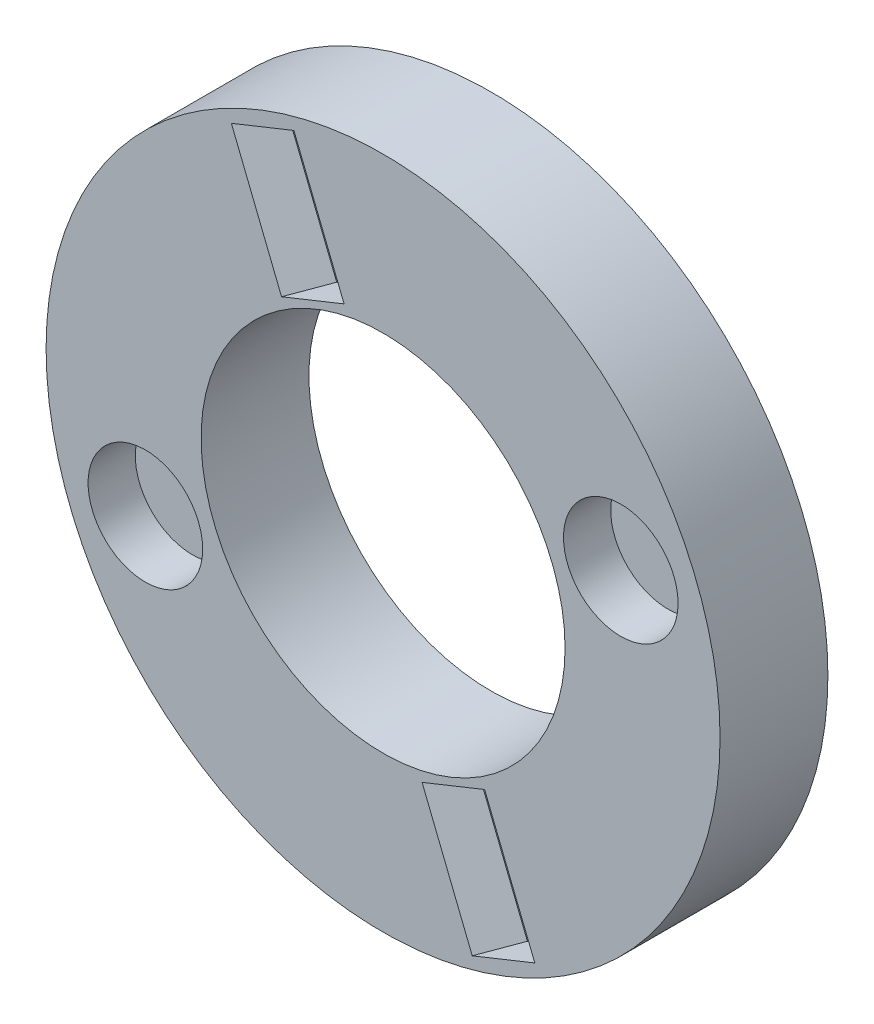
SolidWorks part; units mm, degrees
ref_plane "Plan de face" through (0, 0, 0) normal (0, 0, 1) x (1, 0, 0)
ref_plane "Plan de dessus" through (0, 0, 0) normal (0, 1, 0) x (1, 0, 0)
ref_plane "Plan de droite" through (0, 0, 0) normal (1, 0, 0) x (0, 0, -1)
sketch "Esquisse1" plane through (0, 0, 0) normal (0, 0, 1) x (1, 0, 0)
  circle A0 centre (0, 0) radius 11
  circle A1 centre (0, 0) radius 25
  dimension "D1" = 22
  dimension "D2" = 50
extrude "Boss.-Extru.1" add sketch "Esquisse1" along normal blind 8
sketch "Esquisse2" plane through (0, 0, 8) normal (0, 0, 1) x (1, 0, 0)
  line L0 (-14.7134, 6.2862) -> (-5.9572, 14.8496) construction
  line L1 (-5.9572, 14.8496) -> (6.2896, 14.712) construction
  line L2 (-6.2896, -14.712) -> (5.9572, -14.8496) construction
  line L3 (5.9572, -14.8496) -> (14.7134, -6.2862) construction
  line L4 (-5.9572, 14.8496) -> (0, 0) construction
  line L5 (0, 0) -> (5.9572, -14.8496) construction
  circle A0 centre (0, 0) radius 16 construction
  circle A2 centre (-14.7134, 6.2862) radius 2.5
  circle A3 centre (6.2896, 14.712) radius 2.5
  circle A4 centre (14.7134, -6.2862) radius 2.5
  circle A6 centre (-6.2896, -14.712) radius 2.5
  dimension "D1" = 32
  dimension "D3" = 5
  dimension "D2" = 22.63
sketch "Esquisse5" plane through (0, 0, 8) normal (0, 0, 1) x (1, 0, 0)
  line L0 (23.2025, 9.3082) -> (0, 0) construction
  line L1 (23.2025, 9.3082) -> (14.7134, -6.2862) construction
  line L2 (14.7134, -6.2862) -> (6.2896, 14.712) construction
  line L3 (6.2896, 14.712) -> (23.2025, 9.3082) construction
  circle A2 centre (0, 0) radius 25 construction
ref_plane "Plan1" through (0, 0, 8) normal (-0.9281, -0.3723, 0) x (0, 0, 1)
ref_plane "Plan2" through (0, 0, 0) normal (-0.3723, 0.9281, 0) x (-0.9281, -0.3723, 0)
sketch "Esquisse16" plane through (0, 0, 0) normal (-0.3723, 0.9281, 0) x (-0.9281, -0.3723, 0)
  line L0 (-2.5, 8) -> (2.5, 8)
  line L1 (-25, 8) -> (0, 8) construction
  line L2 (2.5, 8) -> (0.5, 5.7639)
  line L3 (0.5, 5.7639) -> (-0.5, 5.7639)
  line L4 (-0.5, 5.7639) -> (-2.5, 8)
  point P7 (0, 8)
  dimension "D1" = 5
  dimension "D2" = 1
  dimension "D3" = 3
extrude "Enlèv. mat.-Extru.9" cut sketch "Esquisse16" against normal blind 10 from offset 14 offset against normal yes
sketch "Esquisse17" plane through (0, 0, 5.7639) normal (0, 0, 1) x (1, 0, 0)
  line L0 (4.7485, -13.1796) -> (9.3999, -22.0883) construction
mirror "Symétrie4" about plane through (0, 0, 0) normal (-0.3723, 0.9281, 0) of "Enlèv. mat.-Extru.9"
sketch "Esquisse10" plane through (0, 0, 0) normal (0, 0, -1) x (-1, 0, 0)
  line L4 (7.0742, 17.6339) -> (17.6339, -7.0742) construction
  line L5 (17.6339, -7.0742) -> (-7.0742, -17.6339) construction
  line L6 (-7.0742, -17.6339) -> (-17.6339, 7.0742) construction
  line L7 (-17.6339, 7.0742) -> (7.0742, 17.6339) construction
  line L8 (7.0742, 17.6339) -> (-7.0742, -17.6339) construction
  circle A0 centre (7.0742, 17.6339) radius 4.25
  circle A2 centre (-7.0742, -17.6339) radius 4.25
  point P7 (-17.6339, 7.0742)
  point P8 (0, 0)
  point P9 (17.6339, -7.0742)
extrude "Enlèv. mat.-Extru.5" cut sketch "Esquisse10" against normal blind 3.5
sketch "Esquisse12" plane through (0, 0, 8) normal (0, 0, 1) x (1, 0, 0)
  line L0 (17.6339, 7.0742) -> (7.0742, -17.6339) construction
  line L1 (7.0742, -17.6339) -> (-17.6339, -7.0742) construction
  line L2 (-17.6339, -7.0742) -> (-7.0742, 17.6339) construction
  line L3 (-7.0742, 17.6339) -> (17.6339, 7.0742) construction
  line L4 (4.7485, -13.1796) -> (9.3999, -22.0883) construction
  line L5 (17.6339, 7.0742) -> (-17.6339, -7.0742) construction
  circle A0 centre (17.6339, 7.0742) radius 4.25
  circle A1 centre (-17.6339, -7.0742) radius 4.25
  point P2 (0, 0)
  dimension "D1" = 8.5
extrude "Enlèv. mat.-Extru.6" cut sketch "Esquisse12" against normal blind 3.5
sketch "Esquisse13" plane through (0, 0, 8) normal (0, 0, 1) x (1, 0, 0)
  circle A0 centre (0, 0) radius 13.5
  dimension "D1" = 27
extrude "Enlèv. mat.-Extru.7" cut sketch "Esquisse13" against normal blind 10
sketch "Esquisse14" plane through (0, 0, 0) normal (0, 0, -1) x (-1, 0, 0)
  line L0 (7.0742, 17.6339) -> (17.6339, -7.0742) construction
  line L1 (17.6339, -7.0742) -> (-7.0742, -17.6339) construction
  line L3 (-7.0742, -17.6339) -> (-17.6339, 7.0742) construction
  line L4 (-17.6339, 7.0742) -> (7.0742, 17.6339) construction
  line L5 (-4.7485, -13.1796) -> (-9.3999, -22.0883) construction
sketch "Esquisse15" plane through (0, 0, 0) normal (-0.3723, 0.9281, 0) x (-0.9281, -0.3723, 0)
  line L0 (-16.75, 0) -> (-21.25, 0)
  line L1 (-21.25, 0) -> (-20, 2.7272)
  line L2 (-20, 2.7272) -> (-18, 2.7272)
  line L3 (-18, 2.7272) -> (-16.75, 0)
  point P5 (-19, 0)
  dimension "D1" = 4.5
  dimension "D2" = 3
  dimension "D3" = 2
sketch "Esquisse18" plane through (0, 0, 8) normal (-0.9281, -0.3723, 0) x (0, 0, 1)
  line L0 (-8, -2.5) -> (-8, 2.5)
  line L1 (-8, 2.5) -> (-5.7639, 0.5)
  line L2 (-5.7639, 0.5) -> (-5.7639, -0.5)
  line L3 (-5.7639, -0.5) -> (-8, -2.5)
  line L4 (27.7618, 0) -> (-43.7618, 0) construction
  point P6 (-8, 0)
  dimension "D1" = 5
  dimension "D2" = 3
  dimension "D3" = 1
extrude "Enlèv. mat.-Extru.10" cut sketch "Esquisse18" against normal blind 10 from offset 14 offset against normal yes
mirror "Symétrie5" about plane through (0, 0, 8) normal (-0.9281, -0.3723, 0) of "Enlèv. mat.-Extru.10"
